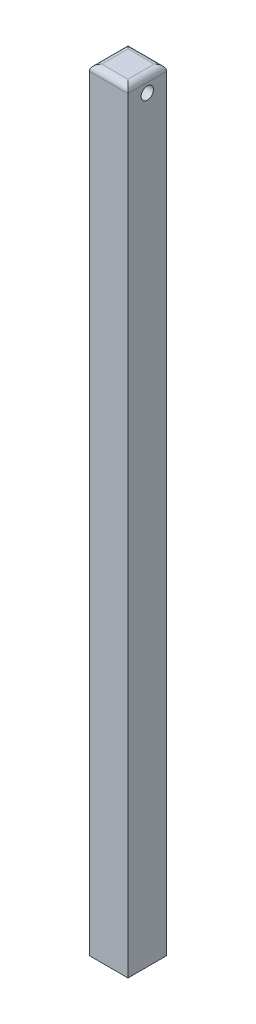
SolidWorks part; units mm, degrees
ref_plane "Front" through (0, 0, 0) normal (0, 0, 1) x (1, 0, 0)
ref_plane "Top" through (0, 0, 0) normal (0, 1, 0) x (1, 0, 0)
ref_plane "Right" through (0, 0, 0) normal (1, 0, 0) x (0, 0, -1)
sketch "Sketch1" plane through (0, 0, 0) normal (0, 0, 1) x (1, 0, 0)
  line L0 (0, 244.3182) -> (0, -255.6818)
  dimension "D1" = 500
sketch3d "3DSketch1"
  line L1 (12.5, -255.6818, -12.5) -> (12.5, -255.6818, 12.5)
  line L2 (12.5, -255.6818, -12.5) -> (-12.5, -255.6818, -12.5)
  line L3 (-12.5, -255.6818, -12.5) -> (-12.5, -255.6818, 12.5)
  line L4 (12.5, -255.6818, 12.5) -> (-12.5, -255.6818, 12.5)
  line L5 (12.5, -255.6818, -12.5) -> (-12.5, -255.6818, 12.5) construction
  line L6 (-12.5, -255.6818, -12.5) -> (12.5, -255.6818, 12.5) construction
  point P0 (0, -255.6818, 0)
  dimension "D1" = 25
  dimension "D2" = 25
sweep "Sweep1" add profiles "3DSketch1" path "Sketch1"
sketch "Sketch2" plane through (12.5, 0, 0) normal (1, 0, 0) x (0, 0, -1)
  line L0 (12.5, 244.3182) -> (-12.5, 244.3182) construction
  circle A0 centre (0, 234.3182) radius 4
  dimension "D1" = 8
  dimension "D2" = 10
extrude "Cut-Extrude1" cut sketch "Sketch2" against normal through all both and the other way through all
fillet "Fillet1" radius 4 4 edges at (-12.5, 244.3182, 0) (12.5, 244.3182, 0) (0, 244.3182, -12.5) (0, 244.3182, 12.5)
scale "Scale1" scale about origin uniform scaling yes scale factor 5
